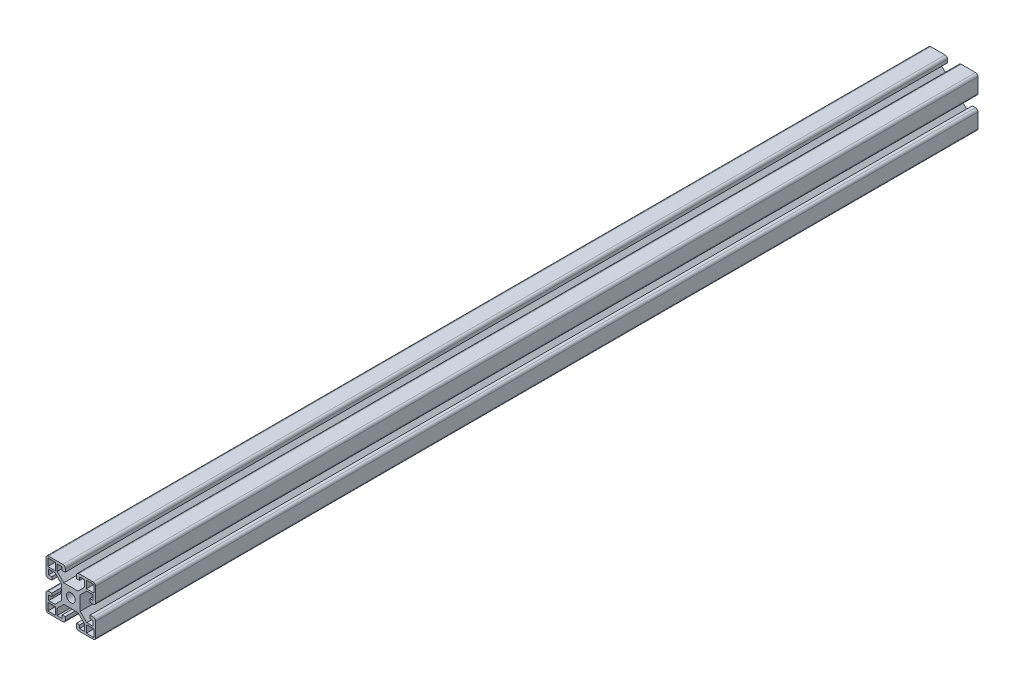
SolidWorks part; units mm, degrees
ref_plane "Alzado" through (0, 0, 0) normal (0, 0, 1) x (1, 0, 0)
ref_plane "Planta" through (0, 0, 0) normal (0, 1, 0) x (1, 0, 0)
ref_plane "Vista lateral" through (0, 0, 0) normal (1, 0, 0) x (0, 0, -1)
sketch "Croquis1" plane through (0, 0, 0) normal (0, 0, 1) x (1, 0, 0)
  line L1 (-20, -20) -> (20, -20)
  line L2 (-20, -20) -> (-20, 20)
  line L3 (-20, 20) -> (20, 20)
  line L4 (20, -20) -> (20, 20)
  line L5 (-20, -20) -> (20, 20) construction
  line L6 (-20, 20) -> (20, -20) construction
  point P0 (0, 0)
  dimension "D1" = 40
  dimension "D2" = 40
extrude "Saliente-Extruir1" add sketch "Croquis1" along normal blind 710
sketch "Croquis2" plane through (0, 0, 710) normal (0, 0, 1) x (1, 0, 0)
  line L0 (-7.5, 7.5) -> (-20, 20) construction
  line L1 (5.7336, -7.5014) -> (-5.7336, -7.5014)
  line L2 (7.5013, -5.7336) -> (7.5013, 5.7336)
  line L3 (5.7336, 7.5014) -> (-5.7336, 7.5014)
  line L4 (-7.5013, -5.7336) -> (-7.5013, 5.7336)
  line L5 (7.5, -7.5) -> (-7.5, 7.5) construction
  line L6 (7.5, 7.5) -> (-7.5, -7.5) construction
  line L7 (-5.7336, 7.5014) -> (-11, 12.7678)
  line L8 (-7.5013, 5.7336) -> (-12.7678, 11)
  line L9 (-20, 20) -> (-20, -20) construction
  line L10 (-18.5, 12.5) -> (-12.5, 12.5)
  line L11 (-18.5, 12.5) -> (-18.5, 18.5)
  line L12 (-18.5, 18.5) -> (-12.5, 18.5)
  line L13 (-12.5, 12.5) -> (-12.5, 18.5)
  line L14 (-18.5, 12.5) -> (-12.5, 18.5) construction
  line L15 (-18.5, 18.5) -> (-12.5, 12.5) construction
  line L16 (-11, 12.7678) -> (-11, 18)
  line L17 (-11, 18) -> (-7, 18)
  line L18 (-7, 18) -> (-7, 15.5)
  line L19 (-7, 15.5) -> (-4.5, 15.5)
  line L20 (-4.5, 15.5) -> (-4.5, 20)
  line L21 (20, 20) -> (-20, 20) construction
  line L22 (0, 20) -> (0, -20) construction
  line L23 (-20, -20) -> (20, -20) construction
  line L24 (-12.7678, 11) -> (-17.8676, 11)
  line L25 (-17.8676, 11) -> (-17.8676, 7)
  line L26 (-17.8676, 7) -> (-15.3676, 7)
  line L27 (-15.3676, 7) -> (-15.3676, 4.5)
  line L28 (-15.3676, 4.5) -> (-20, 4.5)
  line L29 (18.5, 18.5) -> (12.5, 12.5) construction
  line L30 (18.5, 12.5) -> (12.5, 18.5) construction
  line L31 (7.5, 7.5) -> (20, 20) construction
  line L32 (15.3676, 4.5) -> (20, 4.5)
  line L33 (15.3676, 7) -> (15.3676, 4.5)
  line L34 (17.8676, 7) -> (15.3676, 7)
  line L35 (17.8676, 11) -> (17.8676, 7)
  line L36 (12.7678, 11) -> (17.8676, 11)
  line L37 (4.5, 15.5) -> (4.5, 20)
  line L38 (7, 15.5) -> (4.5, 15.5)
  line L39 (7, 18) -> (7, 15.5)
  line L40 (11, 18) -> (7, 18)
  line L41 (11, 12.7678) -> (11, 18)
  line L42 (12.5, 12.5) -> (12.5, 18.5)
  line L43 (18.5, 18.5) -> (12.5, 18.5)
  line L44 (18.5, 12.5) -> (18.5, 18.5)
  line L45 (18.5, 12.5) -> (12.5, 12.5)
  line L46 (7.5013, 5.7336) -> (12.7678, 11)
  line L47 (5.7336, 7.5014) -> (11, 12.7678)
  line L48 (20, 0) -> (-20, 0) construction
  line L49 (20, -20) -> (20, 20) construction
  line L50 (7.5, -7.5) -> (20, -20) construction
  line L51 (18.5, -12.5) -> (12.5, -18.5) construction
  line L52 (18.5, -18.5) -> (12.5, -12.5) construction
  line L53 (-18.5, -18.5) -> (-12.5, -12.5) construction
  line L54 (-18.5, -12.5) -> (-12.5, -18.5) construction
  line L55 (-7.5, -7.5) -> (-20, -20) construction
  line L56 (5.7336, -7.5014) -> (11, -12.7678)
  line L57 (7.5013, -5.7336) -> (12.7678, -11)
  line L58 (18.5, -12.5) -> (12.5, -12.5)
  line L59 (18.5, -12.5) -> (18.5, -18.5)
  line L60 (18.5, -18.5) -> (12.5, -18.5)
  line L61 (12.5, -12.5) -> (12.5, -18.5)
  line L62 (11, -12.7678) -> (11, -18)
  line L63 (11, -18) -> (7, -18)
  line L64 (7, -18) -> (7, -15.5)
  line L65 (7, -15.5) -> (4.5, -15.5)
  line L66 (4.5, -15.5) -> (4.5, -20)
  line L67 (12.7678, -11) -> (17.8676, -11)
  line L68 (17.8676, -11) -> (17.8676, -7)
  line L69 (17.8676, -7) -> (15.3676, -7)
  line L70 (15.3676, -7) -> (15.3676, -4.5)
  line L71 (15.3676, -4.5) -> (20, -4.5)
  line L72 (-15.3676, -4.5) -> (-20, -4.5)
  line L73 (-15.3676, -7) -> (-15.3676, -4.5)
  line L74 (-17.8676, -7) -> (-15.3676, -7)
  line L75 (-17.8676, -11) -> (-17.8676, -7)
  line L76 (-12.7678, -11) -> (-17.8676, -11)
  line L77 (-4.5, -15.5) -> (-4.5, -20)
  line L78 (-7, -15.5) -> (-4.5, -15.5)
  line L79 (-7, -18) -> (-7, -15.5)
  line L80 (-11, -18) -> (-7, -18)
  line L81 (-11, -12.7678) -> (-11, -18)
  line L82 (-12.5, -12.5) -> (-12.5, -18.5)
  line L83 (-18.5, -18.5) -> (-12.5, -18.5)
  line L84 (-18.5, -12.5) -> (-18.5, -18.5)
  line L85 (-18.5, -12.5) -> (-12.5, -12.5)
  line L86 (-7.5013, -5.7336) -> (-12.7678, -11)
  line L87 (-5.7336, -7.5014) -> (-11, -12.7678)
  line L88 (5.7336, -7.5014) -> (-5.7336, -7.5014)
  line L89 (-20, -4.5) -> (-20, 4.5)
  line L90 (20, 4.5) -> (20, -4.5)
  line L91 (-4.5, -20) -> (4.5, -20)
  line L92 (-4.5, 20) -> (4.5, 20)
  circle A0 centre (0, 0) radius 3.5
  point P0 (0, 0)
  point P14 (-15.5, 15.5)
  point P56 (15.5, 15.5)
  point P99 (15.5, -15.5)
  point P100 (-15.5, -15.5)
  line M20 (20, -20) -> (20, 20)
  line M21 (20, 20) -> (-20, 20)
  line M22 (-20, 20) -> (-20, -20)
  line M23 (-20, -20) -> (20, -20)
  dimension "D3" = 7
  dimension "D1" = 15
  dimension "D2" = 15
  dimension "D4" = 1.25
  dimension "D5" = 1.25
  dimension "D6" = 1.5
  dimension "D7" = 6
  dimension "D8" = 6
  dimension "D9" = 1.5
  dimension "D10" = 2
  dimension "D11" = 4
  dimension "D12" = 2.5
  dimension "D13" = 2.5
  dimension "D14" = 1.5
  dimension "D15" = 4
  dimension "D16" = 2.5
  dimension "D17" = 2.5
extrude "Cortar-Extruir2" cut sketch "Croquis2" against normal up to surface (710 mm away) contours L10 L13 L12 L11 | L3 L47 L41 L40 L39 L38 L37 L20 L19 L18 L17 L16 L7 M21 | L45 L44 L43 L42 | L70 L71 L32 L33 L34 L35 L36 L46 L2 L57 L67 L68 L69 M20 | L86 L4 L8 L24 L25 L26 L27 L28 L72 L73 L74 L75 L76 M22 | A0 | L1 L87 L81 L80 L79 L78 L77 L66 L65 L64 L63 L62 L56 M23 | L85 L84 L83 L82 | L58 L61 L60 L59 up to face at (0, 0, 0)
fillet "Redondeo1" radius 2 4 edges at (-20, -20, 355) (-20, 20, 355) (20, -20, 355) (20, 20, 355)
fillet "Redondeo2" radius 2 8 edges at (-20, -4.5, 355) (-20, 4.5, 355) (-4.5, -20, 355) (4.5, -20, 355) (20, 4.5, 355) (20, -4.5, 355) (4.5, 20, 355) (-4.5, 20, 355)
